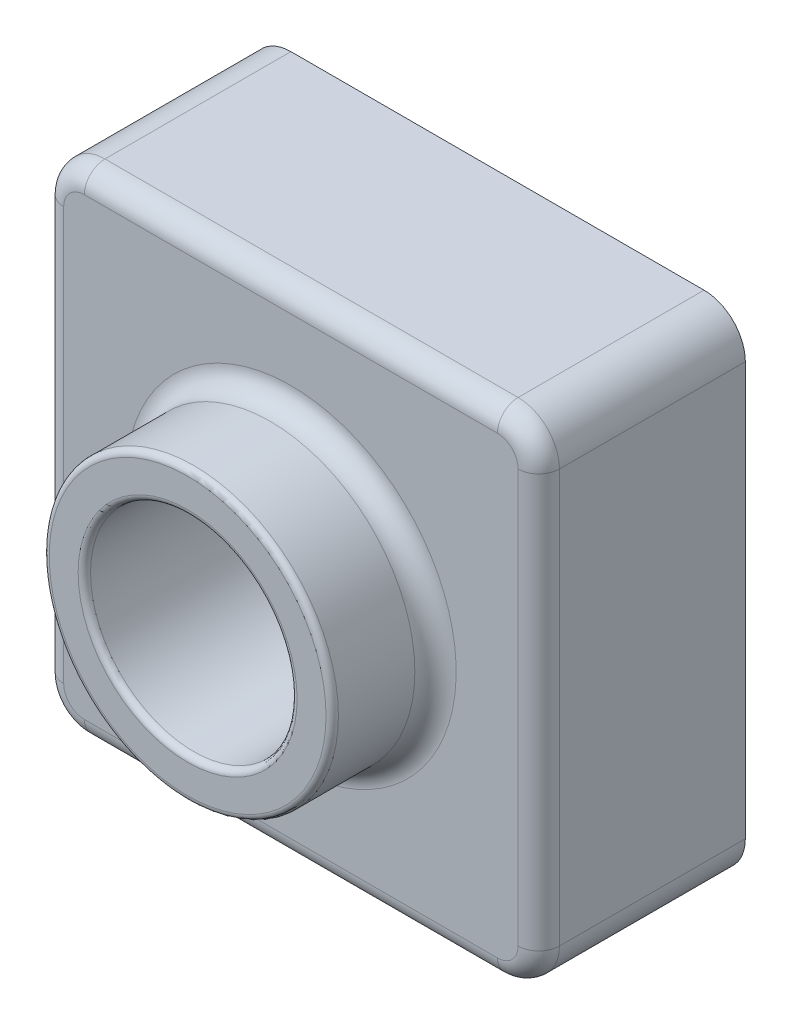
SolidWorks part; units mm, degrees
material "Chrome Stainless Steel"
ref_plane "Front" through (0, 0, 0) normal (0, 0, 1) x (1, 0, 0)
ref_plane "Top" through (0, 0, 0) normal (0, 1, 0) x (1, 0, 0)
ref_plane "Right" through (0, 0, 0) normal (1, 0, 0) x (0, 0, -1)
sketch "Sketch2" plane through (0, 0, 0) normal (0, 0, 1) x (1, 0, 0)
  line L1 (0, 0) -> (120, 0)
  line L2 (0, 0) -> (0, 120)
  line L3 (0, 120) -> (120, 120)
  line L4 (120, 0) -> (120, 120)
  dimension "D1" = 120
  dimension "D2" = 120
extrude "Boss-Extrude1" add sketch "Sketch2" along normal blind 50 contours L3 L4 L1 L2
sketch "Sketch3" plane through (0, 0, 50) normal (0, 0, 1) x (1, 0, 0)
  line L0 (0, 120) -> (120, 120) construction
  line L2 (0, 0) -> (0, 120) construction
  circle A0 centre (60, 60) radius 35
  dimension "D3" = 70
  dimension "D1" = 60
  dimension "D2" = 60
extrude "Boss-Extrude2" add sketch "Sketch3" along normal blind 25
sketch "Sketch4" plane through (0, 0, 75) normal (0, 0, 1) x (1, 0, 0)
  circle A0 centre (60, 60) radius 25
  dimension "D1" = 50
extrude "Cut-Extrude3" cut sketch "Sketch4" against normal through all
fillet "Fillet1" radius 10 4 edges at (120, 0, 25) (0, 0, 25) (0, 120, 25) (120, 120, 25)
fillet "Fillet3" radius 1.5 2 edges at (85, 60, 75) (95, 60, 75)
fillet "Fillet5" radius 5 9 edges at (25, 60, 50) (2.9289, 2.9289, 50) (0, 60, 50) (2.9289, 117.0711, 50) (60, 120, 50) (117.0711, 117.0711, 50) (120, 60, 50) (117.0711, 2.9289, 50) (60, 0, 50)
shell "Shell1" thickness 2
